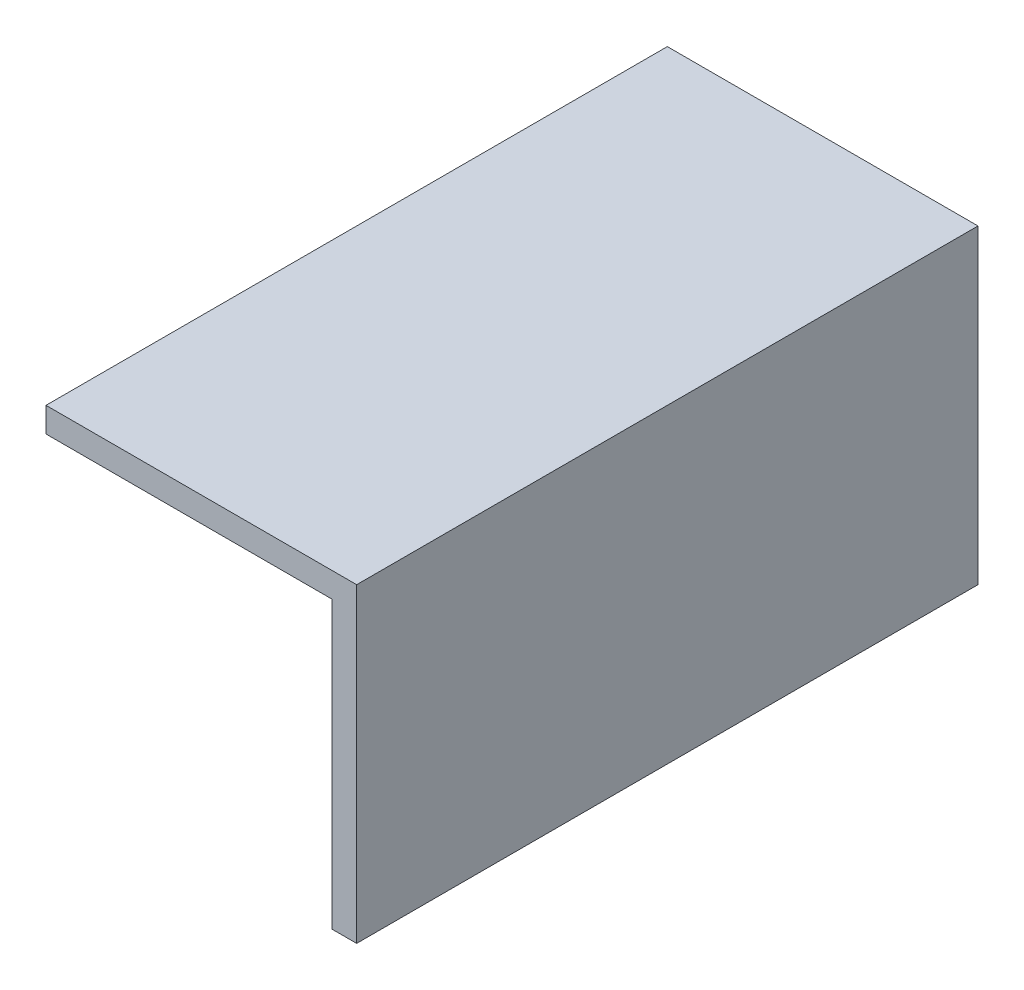
SolidWorks part; units mm, degrees
ref_plane "Alzado" through (0, 0, 0) normal (0, 0, 1) x (1, 0, 0)
ref_plane "Planta" through (0, 0, 0) normal (0, 1, 0) x (1, 0, 0)
ref_plane "Vista lateral" through (0, 0, 0) normal (1, 0, 0) x (0, 0, -1)
sketch "Croquis1" plane through (0, 0, 0) normal (0, 0, 1) x (1, 0, 0)
  line L0 (-124.6107, 44.964) -> (-74.6107, 44.964)
  line L1 (-74.6107, 44.964) -> (-74.6107, -5.036)
  line L2 (-124.6107, 44.964) -> (-124.6107, 40.964)
  line L3 (-124.6107, 40.964) -> (-78.6107, 40.964)
  line L4 (-78.6107, 40.964) -> (-78.6107, -5.036)
  line L5 (-78.6107, -5.036) -> (-74.6107, -5.036)
  dimension "D1" = 50
  dimension "D2" = 50
  dimension "D3" = 4
  dimension "D4" = 4
extrude "Saliente-Extruir2" add sketch "Croquis1" along normal blind 100
